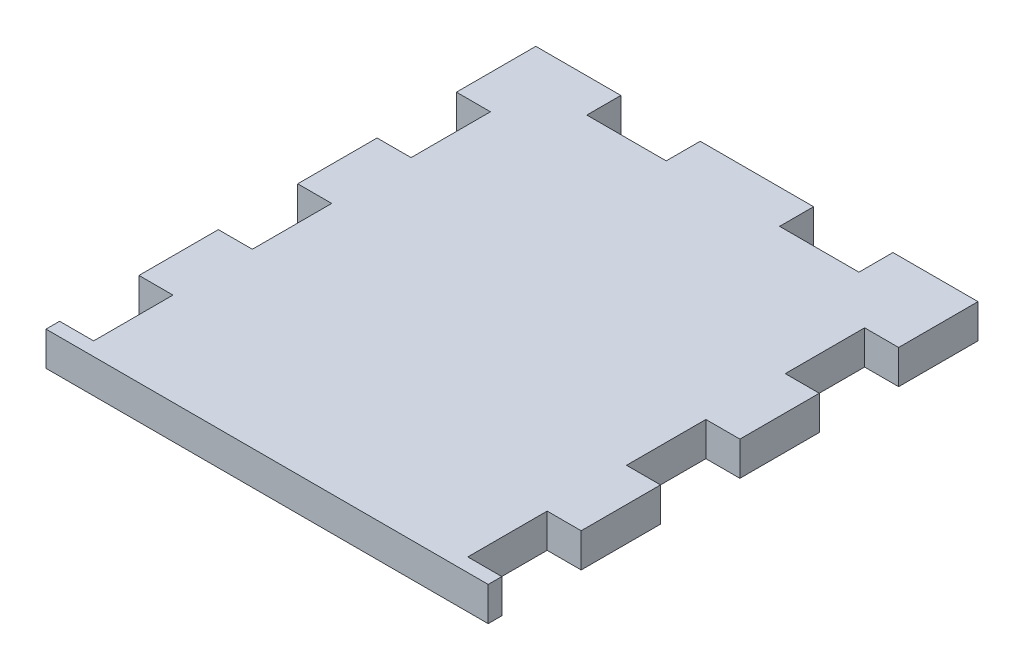
SolidWorks part; units mm, degrees
ref_plane "Front Plane" through (0, 0, 0) normal (0, 0, 1) x (1, 0, 0)
ref_plane "Top Plane" through (0, 0, 0) normal (0, 1, 0) x (1, 0, 0)
ref_plane "Right Plane" through (0, 0, 0) normal (1, 0, 0) x (0, 0, -1)
sketch "Sketch1" plane through (0, 0, 0) normal (0, 1, 0) x (1, 0, 0)
  line L0 (0, 28) -> (0, 21)
  line L1 (0, 0) -> (33, 0)
  line L2 (0, 0) -> (0, 42)
  line L3 (0, 42) -> (33, 42)
  line L4 (33, 0) -> (33, 42)
  line L5 (0, 42) -> (-3, 42)
  line L6 (0, 42) -> (0, 35)
  line L7 (0, 35) -> (-3, 35)
  line L8 (-3, 42) -> (-3, 35)
  line L9 (4.5, 42) -> (11.5, 42)
  line L10 (4.5, 42) -> (4.5, 39)
  line L11 (4.5, 39) -> (11.5, 39)
  line L12 (11.5, 42) -> (11.5, 39)
  line L13 (0, 28) -> (-3, 28)
  line L14 (-3, 28) -> (-3, 21)
  line L15 (0, 21) -> (-3, 21)
  line L16 (0, 14) -> (0, 7)
  line L17 (0, 14) -> (-3, 14)
  line L18 (-3, 14) -> (-3, 7)
  line L19 (0, 7) -> (-3, 7)
  line L20 (0, 42) -> (0, 28) construction
  line L21 (16.5, 42) -> (16.5, 0) construction
  line L22 (-3, 0) -> (36, 0)
  line L23 (-3, 0) -> (-3, -1.2)
  line L24 (-3, -1.2) -> (36, -1.2)
  line L25 (36, 0) -> (36, -1.2)
  line L26 (28.5, 39) -> (21.5, 39)
  line L27 (21.5, 42) -> (21.5, 39)
  line L28 (28.5, 42) -> (21.5, 42)
  line L29 (28.5, 42) -> (28.5, 39)
  line L30 (33, 14) -> (36, 14)
  line L31 (36, 14) -> (36, 7)
  line L32 (33, 7) -> (36, 7)
  line L33 (33, 14) -> (33, 7)
  line L34 (33, 35) -> (36, 35)
  line L35 (36, 42) -> (36, 35)
  line L36 (33, 42) -> (36, 42)
  line L37 (33, 42) -> (33, 35)
  line L38 (33, 28) -> (36, 28)
  line L39 (36, 28) -> (36, 21)
  line L40 (33, 21) -> (36, 21)
  line L41 (33, 28) -> (33, 21)
  dimension "D1" = 33
  dimension "D2" = 3
  dimension "D3" = 3
  dimension "D4" = 7
  dimension "D5" = 7
  dimension "D6" = 42
  dimension "D8" = 14
  dimension "D9" = 1.2
  dimension "D10" = 5
  dimension "D7" = 3
extrude "Boss-Extrude1" add sketch "Sketch1" along normal blind 3 contours L3 L29 L26 L27 L12 L11 L10 L2 L0 L1 L4 | L5 L8 L7 L2 | L15 L0 L13 L14 | L19 L2 L17 L18 | L4 L32 L31 L30 | L4 L40 L39 L38 | L36 L4 L34 L35 | L25 L22 L1 L23 L24
